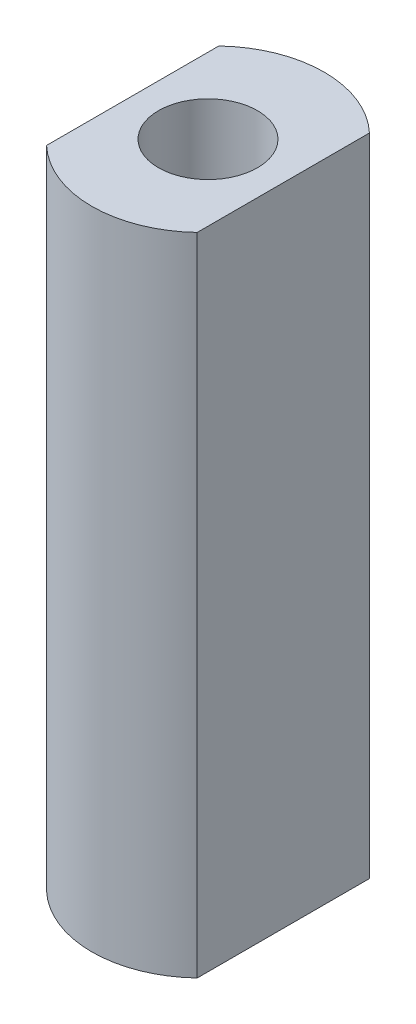
SolidWorks part; units mm, degrees
ref_plane "Front Plane" through (0, 0, 0) normal (0, 0, 1) x (1, 0, 0)
ref_plane "Top Plane" through (0, 0, 0) normal (0, 1, 0) x (1, 0, 0)
ref_plane "Right Plane" through (0, 0, 0) normal (1, 0, 0) x (0, 0, -1)
sketch "Sketch1" plane through (0, 0, 0) normal (0, 1, 0) x (1, 0, 0)
  line L0 (-1.75, 2) -> (-1.75, -2)
  line L2 (-1.75, 0) -> (0, 0) construction
  line L3 (0, 0) -> (0, 2.7) construction
  line L4 (1.75, 2) -> (1.75, -2)
  circle A0 centre (0, 0) radius 1.15
  arc A1 (-1.75, 2) -> (1.75, 2) centre (0, 0.1625) cw
  arc A2 (-1.75, -2) -> (1.75, -2) centre (0, -0.1625) ccw
  point P10 (-1.75, 0)
  dimension "D1" = 2.3
  dimension "D2" = 1.75
  dimension "D3" = 2.7
  dimension "D4" = 4
extrude "Boss-Extrude1" add sketch "Sketch1" along normal blind 15
